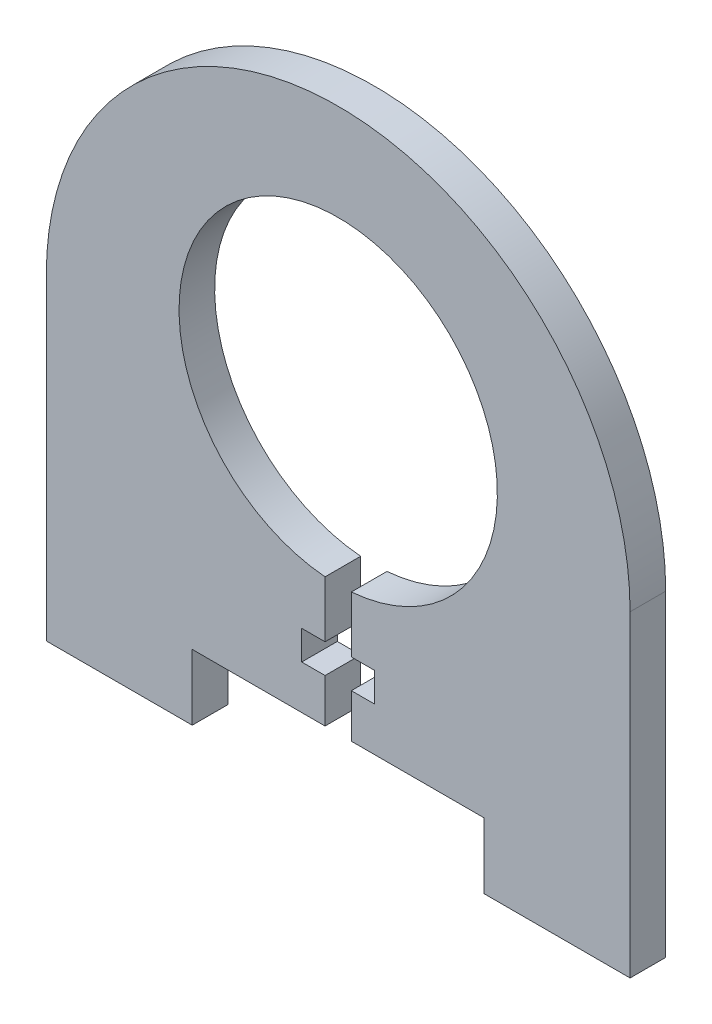
SolidWorks part; units mm, degrees
ref_plane "Front Plane" through (0, 0, 0) normal (0, 0, 1) x (1, 0, 0)
ref_plane "Top Plane" through (0, 0, 0) normal (0, 1, 0) x (1, 0, 0)
ref_plane "Right Plane" through (0, 0, 0) normal (1, 0, 0) x (0, 0, -1)
sketch "Sketch1" plane through (0, 0, 0) normal (0, 0, 1) x (1, 0, 0)
  line L0 (-25.4, 16.9649) -> (25.4, 16.9649) construction
  line L1 (25.4, -13.8001) -> (-25.4, -13.8001)
  line L2 (25.4, -13.8001) -> (25.4, 13.8001)
  line L3 (25.4, 13.8001) -> (-25.4, 13.8001) construction
  line L4 (-25.4, -13.8001) -> (-25.4, 13.8001)
  line L5 (25.4, -13.8001) -> (-25.4, 13.8001) construction
  line L6 (25.4, 13.8001) -> (-25.4, -13.8001) construction
  line L7 (0, 39.2001) -> (0, -13.8001) construction
  arc A0 (-25.4, 13.8001) -> (25.4, 13.8001) centre (0, 13.8001) cw
  circle A3 centre (0, 16.9649) radius 16.5 construction
  circle A4 centre (0, 25.9649) radius 2.5 construction
  point P0 (0, 0)
  dimension "D2" = 33
  dimension "D4" = 5
  dimension "D1" = 30.765
  dimension "D3" = 9
  dimension "D5" = 50.8
  dimension "D6" = 22.2352
extrude "Boss-Extrude1" add sketch "Sketch1" along normal blind 3.0988
sketch "Sketch2" plane through (0, 0, 3.0988) normal (0, 0, 1) x (1, 0, 0)
  circle A0 centre (0, 16.9649) radius 13.85
  dimension "D1" = 27.7
extrude "Cut-Extrude1" cut sketch "Sketch2" against normal up to next
sketch "Sketch3" plane through (0, 0, 3.0988) normal (0, 0, 1) x (1, 0, 0)
  line L0 (25.4, -13.8001) -> (-25.4, -13.8001) construction
  line L1 (-12.7, -13.8001) -> (12.7, -13.8001)
  line L2 (-12.7, -13.8001) -> (-12.7, -8.0851)
  line L3 (-12.7, -8.0851) -> (12.7, -8.0851)
  line L4 (12.7, -13.8001) -> (12.7, -8.0851)
  line L6 (0, 39.2001) -> (0, -13.8001) construction
  point P6 (0, -8.0851)
  dimension "D1" = 5.715
  dimension "D2" = 25.4
extrude "Cut-Extrude2" cut sketch "Sketch3" against normal up to next
sketch "Sketch4" plane through (0, 0, 3.0988) normal (0, 0, 1) x (1, 0, 0)
  line L0 (-25.4, -13.8001) -> (-12.7, -13.8001) construction
  line L1 (25.4, -13.8001) -> (-25.4, -13.8001) construction
  line L2 (-12.7, -8.0851) -> (-12.7, -13.8001) construction
  line L3 (-20.2866, -1014.3325) -> (-20.2866, 48985.6675) construction
  line L4 (0, -1.7043) -> (0, 1.7043) construction
  line L5 (-17.4291, 1.4399) -> (-23.1441, 1.4399)
  line L6 (-17.4291, 1.4399) -> (-17.4291, 7.7899)
  line L7 (-17.4291, 7.7899) -> (-23.1441, 7.7899)
  line L8 (-23.1441, 1.4399) -> (-23.1441, 7.7899)
  line L9 (-17.4291, 1.4399) -> (-23.1441, 7.7899) construction
  line L10 (-17.4291, 7.7899) -> (-23.1441, 1.4399) construction
  line L11 (17.4291, -1.1001) -> (23.1441, -7.4501) construction
  line L12 (-17.4291, -7.4501) -> (-23.1441, -7.4501)
  line L13 (-17.4291, -7.4501) -> (-17.4291, -1.1001)
  line L14 (-17.4291, -1.1001) -> (-23.1441, -1.1001)
  line L15 (-23.1441, -7.4501) -> (-23.1441, -1.1001)
  line L16 (-17.4291, -7.4501) -> (-23.1441, -1.1001) construction
  line L17 (-17.4291, -1.1001) -> (-23.1441, -7.4501) construction
  line L18 (17.4291, -7.4501) -> (23.1441, -1.1001) construction
  line L19 (17.4291, 7.7899) -> (23.1441, 1.4399) construction
  line L20 (17.4291, 1.4399) -> (23.1441, 7.7899) construction
  line L21 (23.1441, -7.4501) -> (23.1441, -1.1001)
  line L22 (17.4291, -1.1001) -> (23.1441, -1.1001)
  line L23 (17.4291, -7.4501) -> (17.4291, -1.1001)
  line L24 (17.4291, -7.4501) -> (23.1441, -7.4501)
  line L25 (23.1441, 1.4399) -> (23.1441, 7.7899)
  line L26 (17.4291, 7.7899) -> (23.1441, 7.7899)
  line L27 (17.4291, 1.4399) -> (17.4291, 7.7899)
  line L28 (17.4291, 1.4399) -> (23.1441, 1.4399)
  point P7 (-20.2866, -13.8001)
  point P9 (-20.2866, 4.6149)
  point P17 (-20.2866, -4.2751)
  point P23 (-19.05, -13.8001)
  point P35 (20.2866, -4.2751)
  point P36 (20.2866, 4.6149)
  dimension "D1" = 6.35
  dimension "D2" = 6.35
  dimension "D3" = 5.715
  dimension "D4" = 5.715
  dimension "D5" = 6.35
  dimension "D6" = 2.54
  dimension "D7" = 1.2366
extrude "Cut-Extrude3" [suppressed] cut sketch "Sketch4" against normal up to next
sketch "Sketch5" plane through (0, 0, 3.0988) normal (0, 0, 1) x (1, 0, 0)
  line L0 (0, 39.2001) -> (0, -13.8001) construction
  line L1 (3.175, -4.2751) -> (1.143, -4.2751)
  line L2 (3.175, -4.2751) -> (3.175, -1.7351)
  line L3 (3.175, -1.7351) -> (1.143, -1.7351)
  line L4 (-3.175, -4.2751) -> (-3.175, -1.7351)
  line L5 (3.175, -4.2751) -> (-3.175, -1.7351) construction
  line L6 (3.175, -1.7351) -> (-3.175, -4.2751) construction
  line L7 (12.7, -8.0851) -> (-12.7, -8.0851) construction
  line L8 (-1.143, -1.7351) -> (-3.175, -1.7351)
  line L9 (-1.143, -8.0851) -> (1.143, -8.0851)
  line L10 (-1.143, -8.0851) -> (-1.143, -4.2751)
  line L11 (-1.143, 5.8849) -> (1.143, 5.8849)
  line L12 (1.143, -8.0851) -> (1.143, -4.2751)
  line L13 (-1.143, -1.7351) -> (-1.143, 5.8849)
  line L14 (1.143, -1.7351) -> (1.143, 5.8849)
  line L15 (-1.143, -4.2751) -> (-3.175, -4.2751)
  point P0 (0, -3.0051)
  point P14 (0, 5.8849)
  dimension "D1" = 6.35
  dimension "D2" = 2.54
  dimension "D3" = 3.81
  dimension "D4" = 2.286
  dimension "D5" = 13.97
extrude "Cut-Extrude4" cut sketch "Sketch5" against normal up to next
equation "\"D2@Sketch1\"=33mm"
equation "\"D1@Sketch1\"=0.75+\"motor offset\"+\"thickness0.25\""
equation "\"t\"=0.225"
equation "\"D1@Boss-Extrude1\"=\"thickness0.125\""
equation "\"D1@Sketch3\"=\"thickness0.25\""
equation "\"D4@Sketch4\"=\"t\""
equation "\"D3@Sketch4\"=\"t\""
equation "\"motor offset\"=6mm"
equation "\"thickness0.25\"=0.225in"
equation "\"thickness0.125\"=0.122in"
